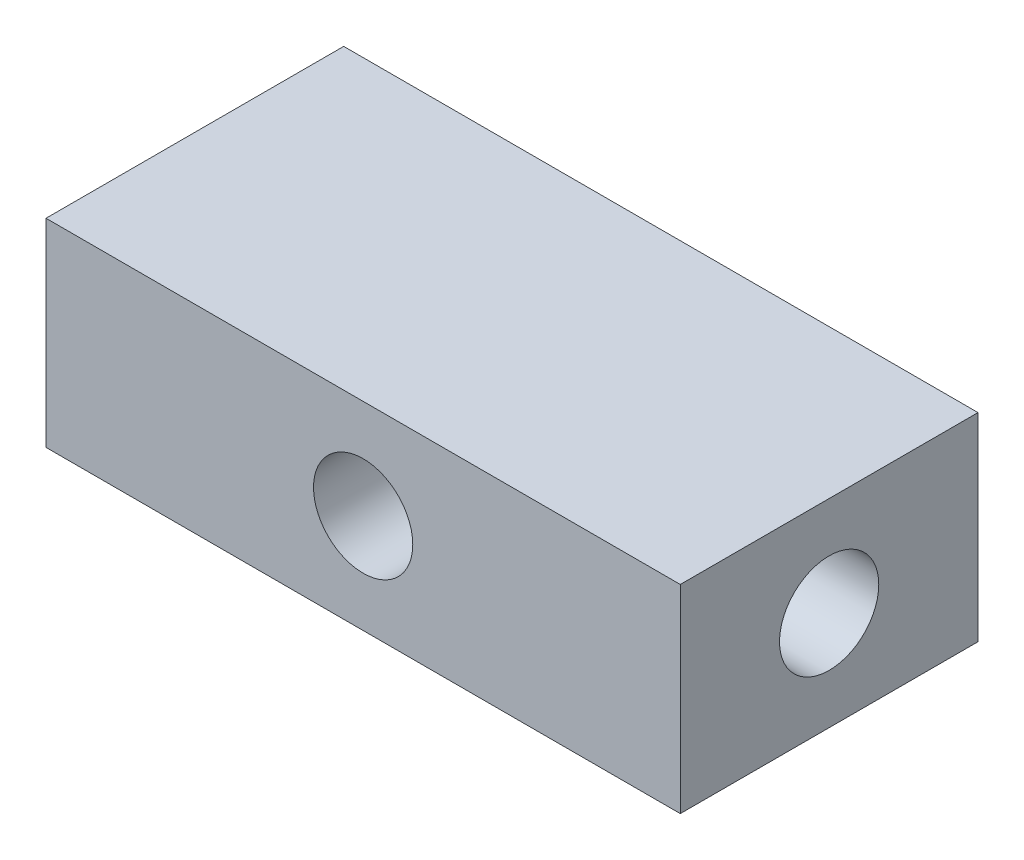
SolidWorks part; units mm, degrees
ref_plane "Piano frontale" through (0, 0, 0) normal (0, 0, 1) x (1, 0, 0)
ref_plane "Piano superiore" through (0, 0, 0) normal (0, 1, 0) x (1, 0, 0)
ref_plane "Piano destro" through (0, 0, 0) normal (1, 0, 0) x (0, 0, -1)
sketch "Schizzo1" plane through (0, 0, 0) normal (0, 1, 0) x (1, 0, 0)
  line L1 (-16, 15) -> (15.9587, 15)
  line L2 (-16, 15) -> (-16, 0)
  line L3 (-16, 0) -> (15.9587, 0)
  line L4 (15.9587, 15) -> (15.9587, 0)
extrude "Estrusione-Estrusione1" add sketch "Schizzo1" against normal blind 10
sketch "Schizzo4" plane through (0, 0, 0) normal (0, 0, 1) x (1, 0, 0)
  line L0 (-16, 0) -> (15.9587, -10) construction
  line L1 (15.9587, 0) -> (-16, -10) construction
  circle A0 centre (-0.0207, -5) radius 2.5
  dimension "D1" = 5
extrude "Taglio-Estrusione1" cut sketch "Schizzo4" against normal through all
sketch "Schizzo5" plane through (15.9587, 0, 0) normal (1, 0, 0) x (0, 0, -1)
  line L0 (0, 0) -> (15, -10) construction
  line L1 (15, 1.4732) -> (0, -10) construction
  circle A0 centre (7.5, -5) radius 2.5
  dimension "D1" = 5
extrude "Taglio-Estrusione2" cut sketch "Schizzo5" against normal through all
